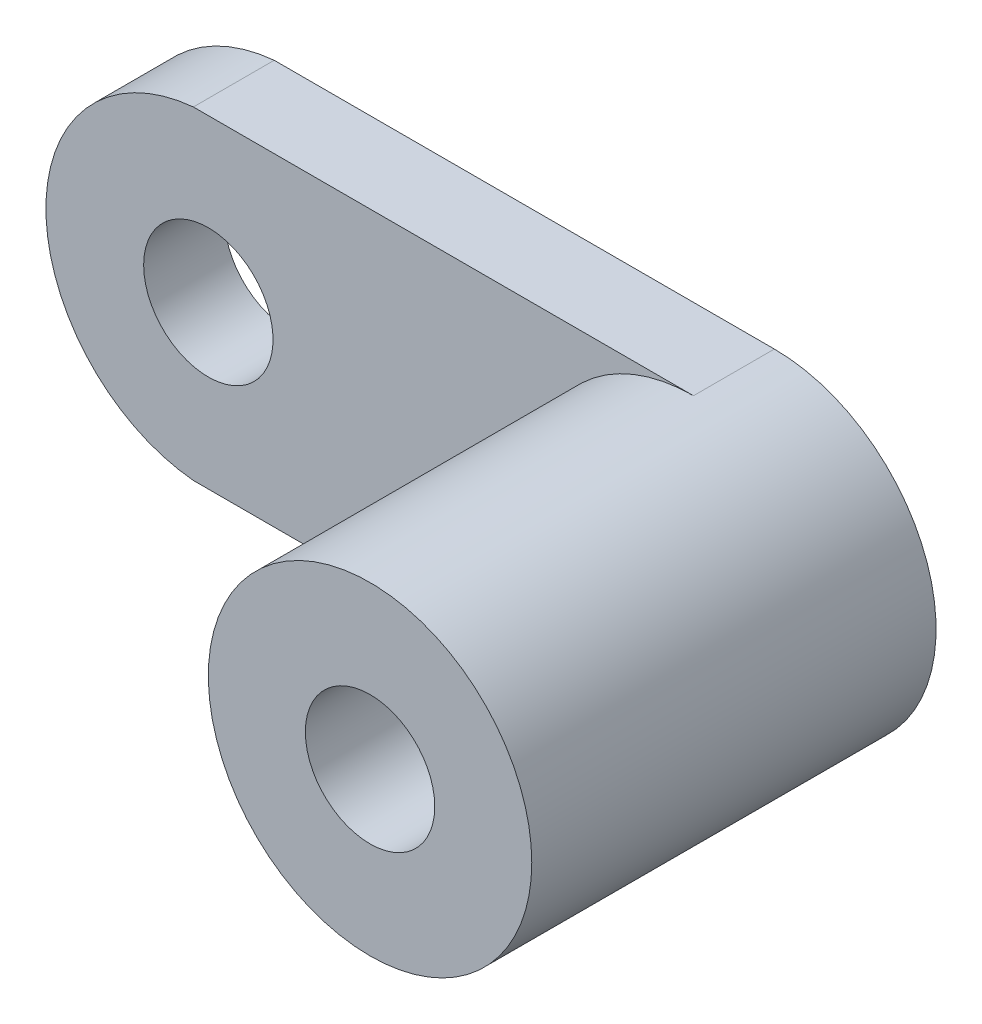
SolidWorks part; units mm, degrees
ref_plane "Front" through (0, 0, 0) normal (0, 0, 1) x (1, 0, 0)
ref_plane "Top" through (0, 0, 0) normal (0, 1, 0) x (1, 0, 0)
ref_plane "Right" through (0, 0, 0) normal (1, 0, 0) x (0, 0, -1)
sketch "Эскиз1" plane through (0, 0, 0) normal (0, 0, 1) x (1, 0, 0)
  circle A0 centre (0, 0) radius 1.6
  circle A1 centre (0, 0) radius 4
extrude "Бобышка-Вытянуть1" add sketch "Эскиз1" along normal blind 8
sketch "Эскиз2" plane through (0, 0, 0) normal (0, 0, -1) x (-1, 0, 0)
  line L0 (0, 0) -> (12, 0) construction
  line L2 (0, -4) -> (12.3704, -4)
  line L4 (0, 4) -> (12.3704, 4)
  circle A0 centre (12, 0) radius 1.6
  arc A4 (0, 4) -> (0, -4) centre (0, 0) ccw
  circle A5 centre (0, 0) radius 1.6
  arc A6 (12.3704, -4) -> (12.3704, 4) centre (12, 0) ccw
  dimension "D1" = 12
extrude "Бобышка-Вытянуть2" add sketch "Эскиз2" along normal blind 2
